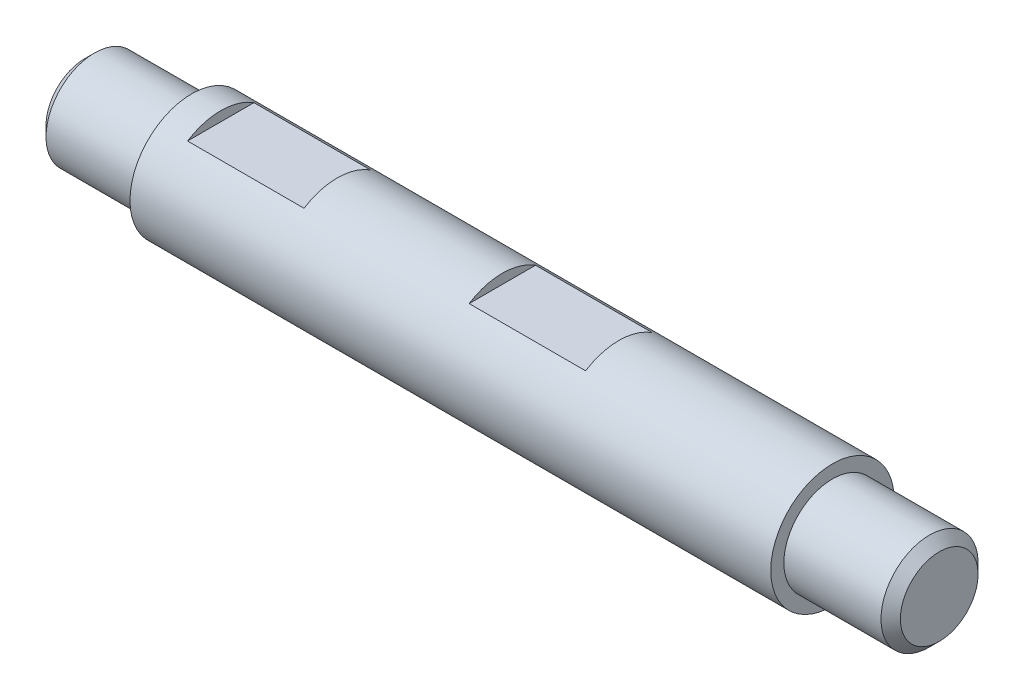
SolidWorks part; units mm, degrees
material "6061 Alloy"
ref_plane "Front Plane" through (0, 0, 0) normal (0, 0, 1) x (1, 0, 0)
ref_plane "Top Plane" through (0, 0, 0) normal (0, 1, 0) x (1, 0, 0)
ref_plane "Right Plane" through (0, 0, 0) normal (1, 0, 0) x (0, 0, -1)
sketch "Sketch2" plane through (0, 0, 0) normal (0, 0, 1) x (1, 0, 0)
  line L0 (0, 0) -> (0, 6.35) construction
  line L1 (33, 6.35) -> (-33, 6.35)
  line L2 (-33, 6.35) -> (-33, 5)
  line L3 (-33, 5) -> (-44, 5)
  line L4 (-44, 5) -> (-44, 0)
  line L5 (33, 5) -> (44, 5)
  line L6 (44, 5) -> (44, 0)
  line L7 (-44, 0) -> (44, 0) construction
  line L8 (33, 6.35) -> (33, 5)
  line L9 (-44, 0) -> (44, 0)
revolve "Revolve1" add sketch "Sketch2" angle 360 about L9
chamfer "Chamfer1" distance 1 angle 45 2 edges at (-44, 0, 5) (44, 0, 5)
sketch "Sketch3" plane through (0, 0, 0) normal (0, 0, 1) x (1, 0, 0)
  line L0 (33, 6.35) -> (11, 6.35) construction
  line L1 (33, 6.35) -> (-33, 6.35) construction
  line L3 (-0.9978, 6.35) -> (-18.0008, 6.35) construction
  line L4 (11, 6.35) -> (-0.9978, 6.35)
  line L5 (11, 6.35) -> (11, 5.3507)
  line L6 (11, 5.3507) -> (-0.9978, 5.3507)
  line L7 (-0.9978, 6.35) -> (-0.9978, 5.3507)
  line L9 (-18.0008, 6.35) -> (-30.0006, 6.35)
  line L10 (-18.0008, 6.35) -> (-18.0008, 5.3507)
  line L11 (-18.0008, 5.3507) -> (-30.0006, 5.3507)
  line L12 (-30.0006, 6.35) -> (-30.0006, 5.3507)
extrude "Cut-Extrude1" cut sketch "Sketch3" along normal through all both and the other way through all
ref_plane "Plane1" through (0, -6.35, 0) normal (0, 1, 0) x (1, 0, 0)
sketch "Sketch6" plane through (0, -6.35, 0) normal (0, 1, 0) x (1, 0, 0)
  line L0 (44, 0) -> (22, 0) construction
  line L1 (44, -4) -> (44, 4) construction
  line L2 (22, 0) -> (22, 2.5) construction
  line L4 (19.5, 2.5) -> (-7.5007, 2.5)
  line L5 (22, 0) -> (22, -0.0064)
  line L6 (19.51, -2.4964) -> (-7.5107, -2.4964)
  line L7 (-10.0007, 0) -> (-10.0007, -0.0064)
  arc A0 (22, 0) -> (19.5, 2.5) centre (19.5, 0) ccw
  arc A1 (19.51, -2.4964) -> (22, -0.0064) centre (19.51, -0.0064) ccw
  arc A2 (-7.5007, 2.5) -> (-10.0007, 0) centre (-7.5007, 0) ccw
  arc A3 (-10.0007, -0.0064) -> (-7.5107, -2.4964) centre (-7.5107, -0.0064) ccw
  dimension "D1" = 2.5
  dimension "D2" = 2.49
  dimension "D3" = 2.5
  dimension "D4" = 2.49
extrude "Cut-Extrude2" cut sketch "Sketch6" along normal blind 3
